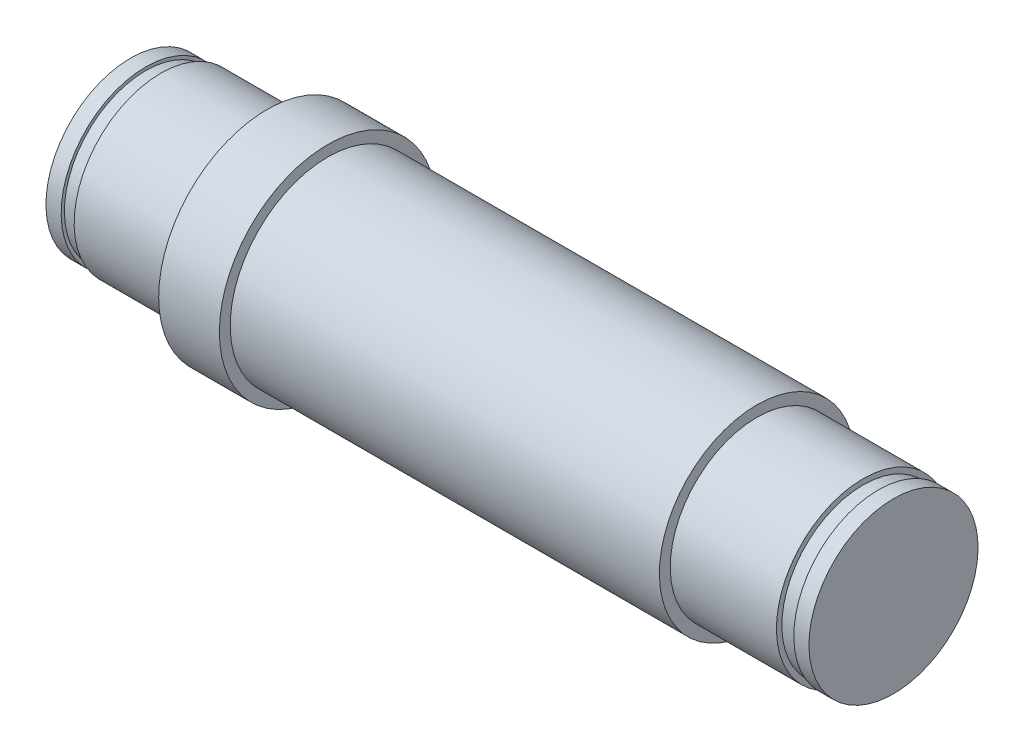
SolidWorks part; units mm, degrees
material "5052-H32"
ref_plane "Front Plane" through (0, 0, 0) normal (0, 0, 1) x (1, 0, 0)
ref_plane "Top Plane" through (0, 0, 0) normal (0, 1, 0) x (1, 0, 0)
ref_plane "Right Plane" through (0, 0, 0) normal (1, 0, 0) x (0, 0, -1)
sketch "Sketch2" plane through (0, 0, 0) normal (0, 0, 1) x (1, 0, 0)
  line L0 (17.6, 0) -> (-17.6, 0)
  line L1 (-17.6, 0) -> (-17.6, 3.9)
  line L2 (-17.6, 3.9) -> (-16.9, 3.9)
  line L3 (-16.9, 3.9) -> (-16.9, 3.75)
  line L4 (-16.9, 3.75) -> (-16.2, 3.75)
  line L5 (-16.2, 3.75) -> (-16.2, 4)
  line L6 (-16.2, 4) -> (-11.3, 4)
  line L7 (-11.3, 4) -> (-11.3, 4.5)
  line L8 (-11.3, 4.5) -> (11.3, 4.5)
  line L9 (11.3, 4.5) -> (11.3, 4)
  line L10 (11.3, 4) -> (16.2, 4)
  line L11 (16.2, 4) -> (16.2, 3.75)
  line L12 (16.2, 3.75) -> (16.9, 3.75)
  line L13 (16.9, 3.75) -> (16.9, 3.9)
  line L14 (16.9, 3.9) -> (17.6, 3.9)
  line L15 (17.6, 3.9) -> (17.6, 0)
  line L16 (23.0089, 0) -> (-24.1917, 0) construction
revolve "Revolve1" add sketch "Sketch2" angle 360 about L16
sketch "Sketch3" plane through (0, 0, 0) normal (1, 0, 0) x (0, 0, -1)
  line L0 (4.0311, -2) -> (4.0311, 2)
  arc A0 (4.0311, 2) -> (4.0311, -2) centre (0, 0) cw
  circle A1 centre (0, 0) radius 4.5 construction
extrude "Cut-Extrude3" [suppressed] cut sketch "Sketch3" against normal up to vertex and the other way up to vertex
sketch "Sketch4" plane through (0, 0, 0) normal (0, 0, 1) x (1, 0, 0)
  line L0 (-11.3, 5) -> (-11.3, 4.5)
  line L1 (-11.3, 4.5) -> (-8.5, 4.5)
  line L2 (-8.5, 4.5) -> (-8.5, 5)
  line L3 (-8.5, 5) -> (-11.3, 5)
  line L4 (0, 0) -> (-1.637, 0) construction
revolve "Revolve2" add sketch "Sketch4" angle 360 about L4
